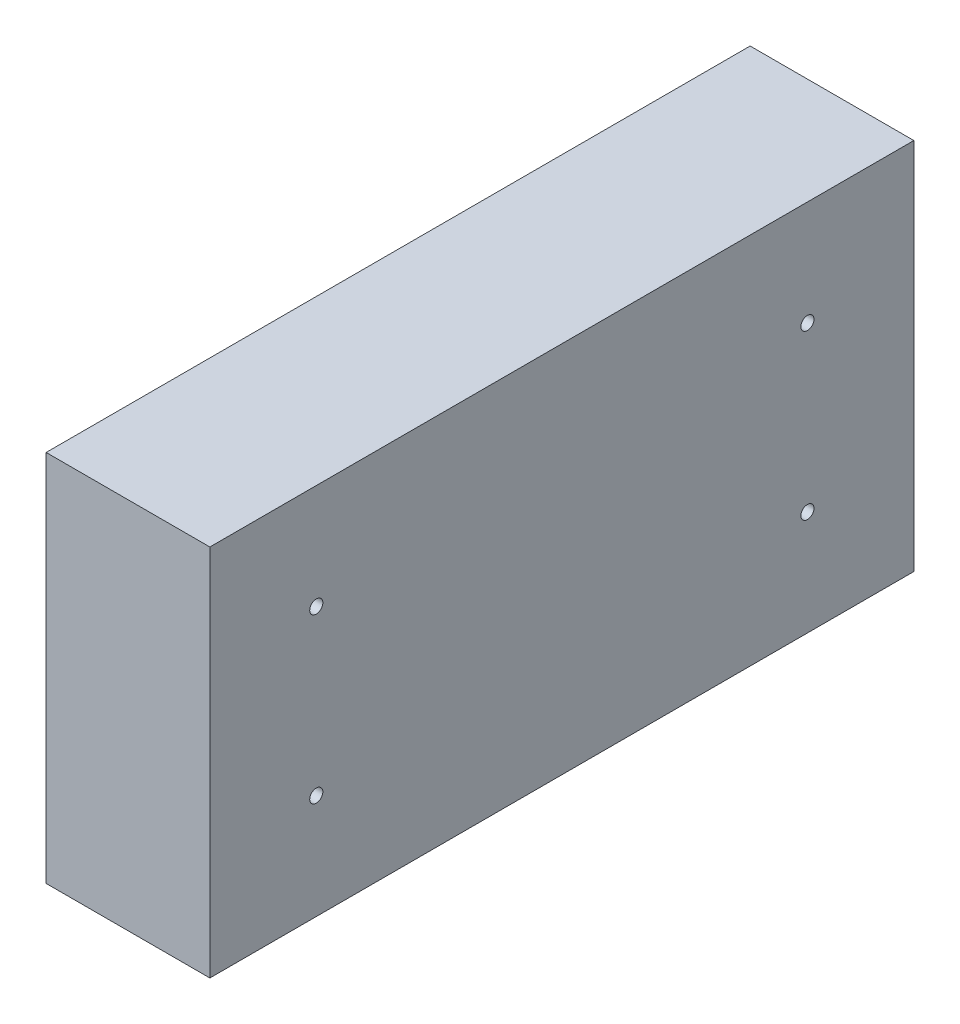
SolidWorks part; units mm, degrees
ref_plane "前视基准面" through (0, 0, 0) normal (0, 0, 1) x (1, 0, 0)
ref_plane "上视基准面" through (0, 0, 0) normal (0, 1, 0) x (1, 0, 0)
ref_plane "右视基准面" through (0, 0, 0) normal (1, 0, 0) x (0, 0, -1)
sketch "草图1" plane through (0, 0, 0) normal (1, 0, 0) x (0, 0, -1)
  line L1 (0, 0) -> (-215, 0)
  line L2 (0, 0) -> (0, 114)
  line L3 (0, 114) -> (-215, 114)
  line L4 (-215, 0) -> (-215, 114)
  dimension "D1" = 215
  dimension "D2" = 114
extrude "凸台-拉伸1" add sketch "草图1" along normal blind 50
sketch "草图2" plane through (0, 0, 0) normal (-1, 0, 0) x (0, 0, 1)
  line L0 (0, 0) -> (0, 114) construction
  line L1 (0, 108.7009) -> (22.3043, 108.7009)
  line L2 (0, 108.7009) -> (0, 5.5325)
  line L3 (0, 5.5325) -> (22.3043, 5.5325)
  line L4 (22.3043, 108.7009) -> (22.3043, 5.5325)
extrude "切除-拉伸1" cut sketch "草图2" against normal blind 40
sketch "草图3" plane through (50, 0, 0) normal (1, 0, 0) x (0, 0, -1)
  line L0 (-182.5, 134.6098) -> (-182.5, -15.0079) construction
  line L1 (-229.1081, 82) -> (22.2775, 82) construction
  line L2 (-32.5, 123.8728) -> (-32.5, -15.0079) construction
  line L3 (16.4422, 32) -> (-241.9458, 32) construction
  line L4 (0, 114) -> (-215, 114) construction
  line L5 (0, 0) -> (0, 114) construction
  circle A0 centre (-182.5, 82) radius 2
  circle A1 centre (-32.5, 82) radius 2
  circle A2 centre (-32.5, 32) radius 2
  circle A3 centre (-182.5, 32) radius 2
  dimension "D1" = 150
  dimension "D2" = 50
  dimension "D3" = 32
  dimension "D4" = 32.5
extrude "切除-拉伸2" cut sketch "草图3" against normal blind 4
